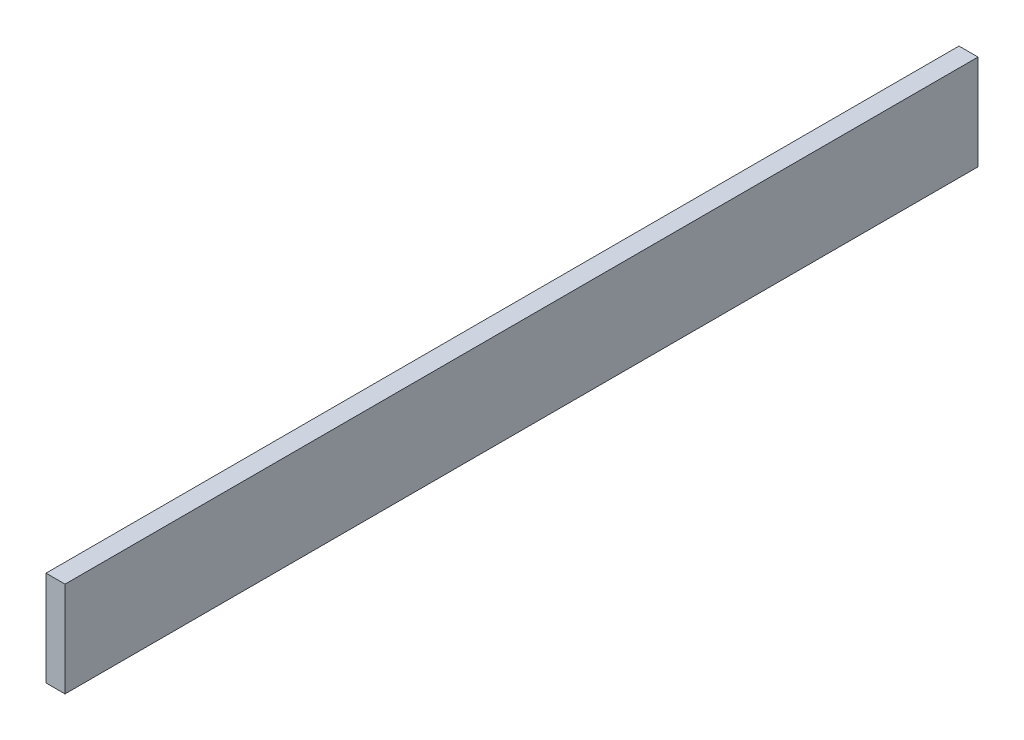
SolidWorks part; units mm, degrees
ref_plane "Front Plane" through (0, 0, 0) normal (0, 0, 1) x (1, 0, 0)
ref_plane "Top Plane" through (0, 0, 0) normal (0, 1, 0) x (1, 0, 0)
ref_plane "Right Plane" through (0, 0, 0) normal (1, 0, 0) x (0, 0, -1)
sketch "Sketch1" plane through (0, 0, 0) normal (0, 0, 1) x (1, 0, 0)
  line L1 (-10, 50) -> (10, 50)
  line L2 (-10, 50) -> (-10, -50)
  line L3 (-10, -50) -> (10, -50)
  line L4 (10, 50) -> (10, -50)
  line L5 (-10, 50) -> (10, -50) construction
  line L6 (-10, -50) -> (10, 50) construction
  point P0 (0, 0)
extrude "Boss-Extrude1" add sketch "Sketch1" along normal blind 960
